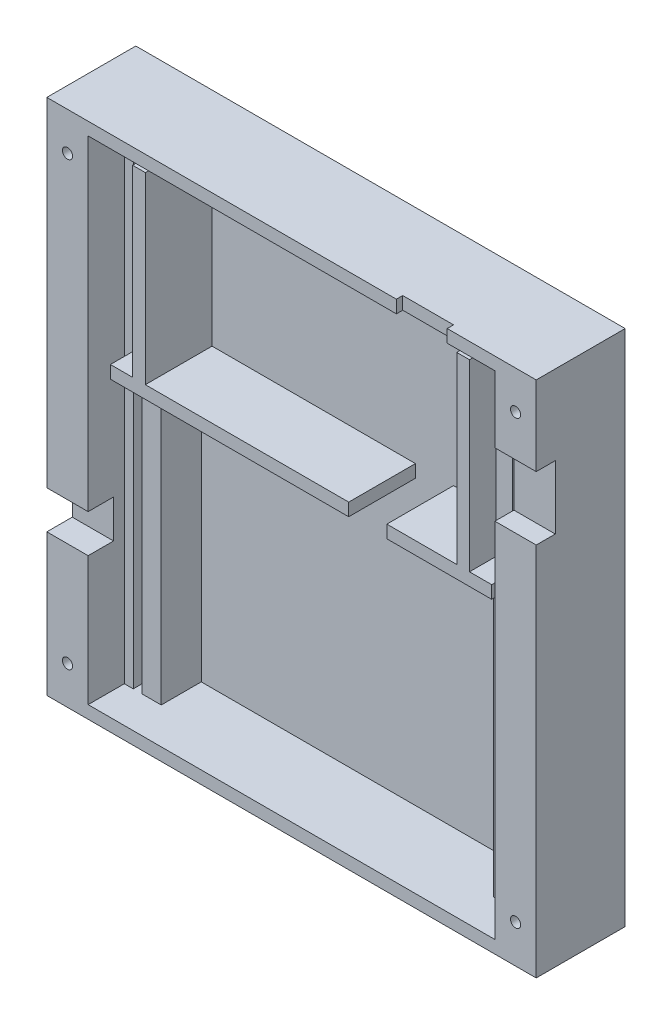
SolidWorks part; units mm, degrees
ref_plane "Front Plane" through (0, 0, 0) normal (1, 0, 0) x (0, 1, 0)
ref_plane "Top Plane" through (0, 0, 0) normal (0, 0, 1) x (0, 1, 0)
ref_plane "Right Plane" through (0, 0, 0) normal (0, 1, 0) x (-1, 0, 0)
sketch "Sketch1" plane through (0, 0, 0) normal (0, 0, 1) x (0, 1, 0)
  line L1 (0, 0) -> (81.5, 0)
  line L2 (0, 0) -> (0, -77)
  line L3 (0, -77) -> (81.5, -77)
  line L4 (81.5, 0) -> (81.5, -77)
extrude "Boss-Extrude1" add sketch "Sketch1" along normal blind 2
sketch "Sketch2" plane through (0, 0, 0) normal (0, 0, 1) x (0, 1, 0)
  line L0 (81.5, -77) -> (81.5, 0) construction
  line L1 (0, 0) -> (81.5, 0)
  line L2 (0, 0) -> (0, -6.5)
  line L3 (0, -6.5) -> (81.5, -6.5)
  line L4 (81.5, 0) -> (81.5, -6.5)
extrude "Boss-Extrude2" add sketch "Sketch2" along normal blind 10
sketch "Sketch3" plane through (0, 0, 0) normal (0, 0, 1) x (0, 1, 0)
  line L0 (0, -6.5) -> (81.5, -6.5) construction
  line L1 (0, 0) -> (22.3, 0)
  line L2 (0, 0) -> (0, -6.5)
  line L3 (0, -6.5) -> (22.3, -6.5)
  line L4 (22.3, 0) -> (22.3, -6.5)
extrude "Boss-Extrude3" add sketch "Sketch3" along normal blind 14
sketch "Sketch4" plane through (0, 0, 0) normal (0, 0, 1) x (0, 1, 0)
  line L0 (81.5, 0) -> (22.3, 0) construction
  line L1 (28.3, 0) -> (81.5, 0)
  line L2 (28.3, 0) -> (28.3, -6.5)
  line L3 (28.3, -6.5) -> (81.5, -6.5)
  line L4 (81.5, 0) -> (81.5, -6.5)
extrude "Boss-Extrude4" add sketch "Sketch4" along normal blind 14
sketch "Sketch5" plane through (0, 0, 0) normal (0, 0, 1) x (0, 1, 0)
  line L0 (0, -6.5) -> (0, -77) construction
  line L1 (0, -70.5) -> (81.5, -70.5)
  line L2 (0, -70.5) -> (0, -77)
  line L3 (0, -77) -> (81.5, -77)
  line L4 (81.5, -70.5) -> (81.5, -77)
extrude "Boss-Extrude5" add sketch "Sketch5" along normal blind 11
sketch "Sketch6" plane through (0, 0, 0) normal (0, 0, 1) x (0, 1, 0)
  line L0 (0, -77) -> (81.5, -77) construction
  line L1 (0, -70.5) -> (59, -70.5)
  line L2 (0, -70.5) -> (0, -77)
  line L3 (0, -77) -> (59, -77)
  line L4 (59, -70.5) -> (59, -77)
extrude "Boss-Extrude6" add sketch "Sketch6" along normal blind 14
sketch "Sketch7" plane through (0, 0, 0) normal (0, 0, 1) x (0, 1, 0)
  line L0 (0, -70.5) -> (81.5, -70.5) construction
  line L1 (69, -70.5) -> (81.5, -70.5)
  line L2 (69, -70.5) -> (69, -77)
  line L3 (69, -77) -> (81.5, -77)
  line L4 (81.5, -70.5) -> (81.5, -77)
extrude "Boss-Extrude7" add sketch "Sketch7" along normal blind 14
sketch "Sketch8" plane through (0, 0, 0) normal (0, 0, 1) x (0, 1, 0)
  line L0 (0, -70.5) -> (81.5, -70.5) construction
  line L1 (0, -6.5) -> (2, -6.5)
  line L2 (0, -6.5) -> (0, -70.5)
  line L3 (0, -70.5) -> (2, -70.5)
  line L4 (2, -6.5) -> (2, -70.5)
extrude "Boss-Extrude8" add sketch "Sketch8" along normal blind 14
sketch "Sketch9" plane through (0, 0, 0) normal (0, 0, 1) x (0, 1, 0)
  line L0 (28.3, -6.5) -> (81.5, -6.5) construction
  line L1 (79.5, -6.5) -> (81.5, -6.5)
  line L2 (79.5, -6.5) -> (79.5, -70.5)
  line L3 (79.5, -70.5) -> (81.5, -70.5)
  line L4 (81.5, -6.5) -> (81.5, -70.5)
extrude "Boss-Extrude9" add sketch "Sketch9" along normal blind 13
sketch "Sketch10" plane through (0, 0, 0) normal (0, 0, 1) x (0, 1, 0)
  line L0 (28.3, -6.5) -> (81.5, -6.5) construction
  line L1 (79.5, -6.5) -> (81.5, -6.5)
  line L2 (79.5, -6.5) -> (79.5, -55)
  line L3 (79.5, -55) -> (81.5, -55)
  line L4 (81.5, -6.5) -> (81.5, -55)
  line L5 (81.5, -70.5) -> (81.5, -6.5) construction
extrude "Boss-Extrude10" add sketch "Sketch10" along normal blind 14
sketch "Sketch11" plane through (0, 0, 0) normal (0, 0, 1) x (0, 1, 0)
  line L0 (79.5, -70.5) -> (79.5, -6.5) construction
  line L1 (79.5, -63) -> (81.5, -63)
  line L2 (79.5, -63) -> (79.5, -70.5)
  line L3 (79.5, -70.5) -> (81.5, -70.5)
  line L4 (81.5, -63) -> (81.5, -70.5)
extrude "Boss-Extrude11" add sketch "Sketch11" along normal blind 14
sketch "Sketch12" plane through (0, 0, 0) normal (0, 0, 1) x (0, 1, 0)
  line L0 (79.5, -70.5) -> (79.5, -6.5) construction
  line L1 (2, -6.5) -> (79.5, -6.5)
  line L2 (2, -6.5) -> (2, -7.9)
  line L3 (2, -7.9) -> (79.5, -7.9)
  line L4 (79.5, -6.5) -> (79.5, -7.9)
extrude "Boss-Extrude12" add sketch "Sketch12" along normal blind 8.3
sketch "Sketch13" plane through (0, 0, 0) normal (0, 0, 1) x (0, 1, 0)
  line L0 (2, -70.5) -> (2, -6.5) construction
  line L1 (2, -9.3) -> (79.5, -9.3)
  line L2 (2, -9.3) -> (2, -12.3)
  line L3 (2, -12.3) -> (79.5, -12.3)
  line L4 (79.5, -9.3) -> (79.5, -12.3)
  line L5 (79.5, -70.5) -> (79.5, -7.9) construction
extrude "Boss-Extrude13" add sketch "Sketch13" along normal blind 8.3
sketch "Sketch14" plane through (0, 0, 0) normal (0, 0, 1) x (0, 1, 0)
  line L0 (2, -70.5) -> (2, -6.5) construction
  line L1 (2, -64.6) -> (79.5, -64.6)
  line L2 (2, -64.6) -> (2, -67.6)
  line L3 (2, -67.6) -> (79.5, -67.6)
  line L4 (79.5, -64.6) -> (79.5, -67.6)
  line L5 (79.5, -70.5) -> (79.5, -12.3) construction
extrude "Boss-Extrude14" add sketch "Sketch14" along normal blind 8.3
sketch "Sketch15" plane through (0, 0, 0) normal (0, 0, 1) x (0, 1, 0)
  line L0 (2, -70.5) -> (2, -6.5) construction
  line L1 (2, -69) -> (79.5, -69)
  line L2 (2, -69) -> (2, -70.5)
  line L3 (2, -70.5) -> (79.5, -70.5)
  line L4 (79.5, -69) -> (79.5, -70.5)
extrude "Boss-Extrude15" add sketch "Sketch15" along normal blind 8.3
sketch "Sketch16" plane through (0, 0, 0) normal (0, 0, 1) x (0, 1, 0)
  line L1 (46.6, -8.5) -> (48.6, -8.5)
  line L2 (46.6, -8.5) -> (46.6, -46)
  line L3 (46.6, -46) -> (48.6, -46)
  line L4 (48.6, -8.5) -> (48.6, -46)
extrude "Boss-Extrude16" add sketch "Sketch16" along normal blind 12.5
sketch "Sketch17" plane through (0, 0, 0) normal (0, 0, 1) x (0, 1, 0)
  line L1 (46.6, -52) -> (48.6, -52)
  line L2 (46.6, -52) -> (46.6, -68.5)
  line L3 (46.6, -68.5) -> (48.6, -68.5)
  line L4 (48.6, -52) -> (48.6, -68.5)
extrude "Boss-Extrude17" add sketch "Sketch17" along normal blind 12.5
sketch "Sketch18" plane through (0, 0, 0) normal (0, 0, 1) x (0, 1, 0)
  line L0 (48.6, -46) -> (48.6, -8.5) construction
  line L1 (48.6, -12) -> (77.5, -12)
  line L2 (48.6, -12) -> (48.6, -14)
  line L3 (48.6, -14) -> (77.5, -14)
  line L4 (77.5, -12) -> (77.5, -14)
extrude "Boss-Extrude18" add sketch "Sketch18" along normal blind 12.5
sketch "Sketch19" plane through (0, 0, 0) normal (0, 0, 1) x (0, 1, 0)
  line L0 (48.6, -68.5) -> (48.6, -52) construction
  line L1 (48.6, -63) -> (77.5, -63)
  line L2 (48.6, -63) -> (48.6, -65)
  line L3 (48.6, -65) -> (77.5, -65)
  line L4 (77.5, -63) -> (77.5, -65)
extrude "Boss-Extrude19" add sketch "Sketch19" along normal blind 12.5
sketch "Sketch20" plane through (0, 0, 0) normal (0, 0, 1) x (0, 1, 0)
  circle A0 centre (6, -3.25) radius 0.8
extrude "Cut-Extrude1" cut sketch "Sketch20" along normal blind 20
sketch "Sketch21" plane through (0, 0, 0) normal (0, 0, 1) x (0, 1, 0)
  circle A0 centre (75.5, -3.25) radius 0.8
extrude "Cut-Extrude2" cut sketch "Sketch21" along normal blind 20
sketch "Sketch22" plane through (0, 0, 0) normal (0, 0, 1) x (0, 1, 0)
  circle A0 centre (6, -73.75) radius 0.8
extrude "Cut-Extrude3" cut sketch "Sketch22" along normal blind 20
sketch "Sketch23" plane through (0, 0, 0) normal (0, 0, 1) x (0, 1, 0)
  circle A0 centre (75.5, -73.75) radius 0.8
extrude "Cut-Extrude4" cut sketch "Sketch23" along normal blind 20
